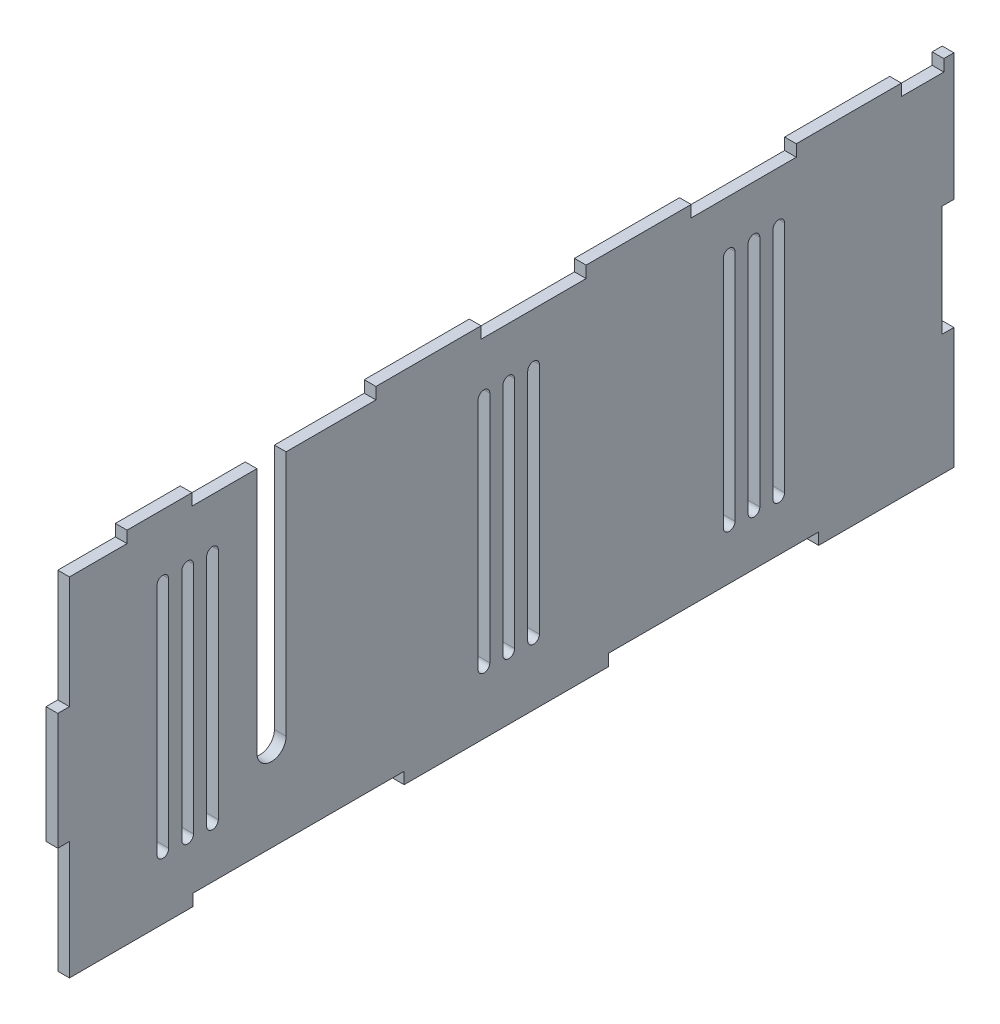
SolidWorks part; units mm, degrees
ref_plane "Front Plane" through (0, 0, 0) normal (0, 0, 1) x (1, 0, 0)
ref_plane "Top Plane" through (0, 0, 0) normal (0, 1, 0) x (1, 0, 0)
ref_plane "Right Plane" through (0, 0, 0) normal (1, 0, 0) x (0, 0, -1)
sketch "Sketch1" plane through (0, 0, 0) normal (1, 0, 0) x (0, 0, -1)
  line L1 (0, 0) -> (307, 0)
  line L2 (0, 0) -> (0, 115)
  line L3 (0, 115) -> (307, 115)
  line L4 (307, 0) -> (307, 115)
  dimension "D1" = 307
  dimension "D2" = 115
extrude "Boss-Extrude1" add sketch "Sketch1" along normal blind 4
sketch "Sketch2" plane through (0, 0, 0) normal (-1, 0, 0) x (0, 0, 1)
  line L0 (-73.2167, 30.5919) -> (-73.2167, 113) construction
  line L1 (-78.2167, 30.5919) -> (-78.2167, 118.2888)
  line L2 (-68.2167, 30.5919) -> (-68.2167, 118.2888)
  line L3 (-139, 113) -> (-121, 113) construction
  line L4 (-78.2167, 118.2888) -> (-68.2167, 118.2888)
  arc A0 (-78.2167, 30.5919) -> (-68.2167, 30.5919) centre (-73.2167, 30.5919) ccw
  point P2 (-73.2167, 71.796)
  dimension "D1" = 10
extrude "Cut-Extrude1" cut sketch "Sketch2" against normal blind 4
sketch "Sketch3" plane through (0, 0, 0) normal (-1, 0, 0) x (0, 0, 1)
  line L0 (0, 36.5) -> (0, -4)
  line L1 (0, 115) -> (-4, 115)
  line L2 (0, 115) -> (0, 76.5)
  line L3 (0, 76.5) -> (-4, 76.5)
  line L4 (-4, 115) -> (-4, 76.5)
  line L9 (0, 36.5) -> (-4, 36.5)
  line L10 (-4, 36.5) -> (-4, -4)
  line L11 (0, 115) -> (0, 0) construction
  line L12 (-68.2167, 115) -> (0, 115) construction
  line L13 (0, -4) -> (-4, -4)
  dimension "D1" = 4
  dimension "D2" = 38.5
  dimension "D3" = 40
extrude "Cut-Extrude2" cut sketch "Sketch3" against normal blind 4
sketch "Sketch4" plane through (0, 0, 0) normal (-1, 0, 0) x (0, 0, 1)
  line L1 (-307, 0) -> (-260.6667, 0)
  line L2 (-307, 0) -> (-307, -4)
  line L3 (-307, -4) -> (-260.6667, -4)
  line L4 (-260.6667, 0) -> (-260.6667, -4)
  line L11 (-4, 0) -> (-46.33, 0)
  line L12 (-4, 0) -> (-4, -4)
  line L13 (-4, -4) -> (-46.33, -4)
  line L14 (-46.33, 0) -> (-46.33, -4)
  dimension "D1" = 46.3333
  dimension "D2" = 4
  dimension "D3" = 42.33
  dimension "D4" = 4
extrude "Boss-Extrude3" add sketch "Sketch4" against normal blind 4 contours L2 L1 L4 L3 | L12 L11 L14 L13
sketch "Sketch5" plane through (0, 0, 0) normal (-1, 0, 0) x (0, 0, 1)
  line L0 (-307, 115) -> (-78.2167, 115) construction
  line L1 (-289, 115) -> (-253, 115)
  line L2 (-289, 115) -> (-289, 119)
  line L3 (-289, 119) -> (-253, 119)
  line L4 (-253, 115) -> (-253, 119)
  line L5 (-307, -4) -> (-307, 115) construction
  dimension "D1" = 4
  dimension "D2" = 36
  dimension "D3" = 18
extrude "Boss-Extrude4" add sketch "Sketch5" against normal blind 4
sketch "Sketch7" plane through (0, 0, 0) normal (-1, 0, 0) x (0, 0, 1)
  line L0 (-68.2167, 115) -> (-4, 115) construction
  line L1 (-45.9767, 115) -> (-23.7367, 115)
  line L2 (-45.9767, 115) -> (-45.9767, 119)
  line L3 (-45.9767, 119) -> (-23.7367, 119)
  line L4 (-23.7367, 115) -> (-23.7367, 119)
  line L5 (-68.2167, 30.5919) -> (-68.2167, 115) construction
  dimension "D1" = 22.24
  dimension "D2" = 22.24
  dimension "D3" = 4
extrude "Boss-Extrude6" add sketch "Sketch7" against normal blind 4
sketch "Sketch8" plane through (0, 0, 0) normal (-1, 0, 0) x (0, 0, 1)
  line L0 (-307, -4) -> (-307, 115) construction
  line L1 (-307, 75.5) -> (-303, 75.5)
  line L2 (-307, 75.5) -> (-307, 37.5)
  line L3 (-307, 37.5) -> (-303, 37.5)
  line L4 (-303, 75.5) -> (-303, 37.5)
  line L5 (-307, 115) -> (-289, 115) construction
  dimension "D1" = 38
  dimension "D2" = 39.5
extrude "Cut-Extrude3" cut sketch "Sketch8" against normal blind 4
pattern_linear "LPattern1" count 3 spacing 72 along (0, 0, 1) of "Boss-Extrude4"
sketch "Sketch9" plane through (0, 0, 0) normal (-1, 0, 0) x (0, 0, 1)
  line L0 (-46.33, 0) -> (-260.6667, 0) construction
  line L1 (-188.6667, 0) -> (-118.6667, 0)
  line L2 (-188.6667, 0) -> (-188.6667, -4)
  line L3 (-188.6667, -4) -> (-118.6667, -4)
  line L4 (-118.6667, 0) -> (-118.6667, -4)
  line L5 (-260.6667, 0) -> (-260.6667, -4) construction
  point P6 (-153.6667, 0)
  dimension "D1" = 70
  dimension "D2" = 107
  dimension "D3" = 4
extrude "Boss-Extrude7" add sketch "Sketch9" against normal blind 4
sketch "Sketch10" plane through (0, 0, 0) normal (-1, 0, 0) x (0, 0, 1)
  line L0 (-247, 97.5) -> (-247, 17.5) construction
  line L1 (-245, 97.5) -> (-245, 17.5)
  line L2 (-249, 97.5) -> (-249, 17.5)
  line L3 (-307, 75.5) -> (-307, 115) construction
  line L4 (-307, -4) -> (-260.6667, -4) construction
  line L6 (-240.5, 97.5) -> (-240.5, 17.5)
  line L7 (-236.5, 97.5) -> (-236.5, 17.5)
  line L8 (-238.5, 97.5) -> (-238.5, 17.5) construction
  line L9 (-232, 97.5) -> (-232, 17.5)
  line L10 (-228, 97.5) -> (-228, 17.5)
  line L11 (-230, 97.5) -> (-230, 17.5) construction
  arc A0 (-245, 97.5) -> (-249, 97.5) centre (-247, 97.5) ccw
  arc A1 (-249, 17.5) -> (-245, 17.5) centre (-247, 17.5) ccw
  arc A2 (-236.5, 97.5) -> (-240.5, 97.5) centre (-238.5, 97.5) ccw
  arc A3 (-240.5, 17.5) -> (-236.5, 17.5) centre (-238.5, 17.5) ccw
  arc A4 (-228, 97.5) -> (-232, 97.5) centre (-230, 97.5) ccw
  arc A5 (-232, 17.5) -> (-228, 17.5) centre (-230, 17.5) ccw
  point P2 (-247, 57.5)
  point P17 (-238.5, 57.5)
  point P24 (-230, 57.5)
  dimension "D1" = 4
  dimension "D2" = 58
  dimension "D3" = 80
  dimension "D4" = 61.5
extrude "Cut-Extrude4" cut sketch "Sketch10" against normal blind 4
pattern_linear "LPattern2" count 2 spacing 84 along (0, 0, 1) of "Cut-Extrude4"
pattern_linear "LPattern3" count 2 spacing 194 along (0, 0, 1) of "Cut-Extrude4"
sketch "Sketch11" plane through (0, 115, 0) normal (0, 1, 0) x (1, 0, 0)
  line L0 (0, 307) -> (0, 289) construction
  line L1 (4, 307) -> (0, 307)
  line L2 (4, 307) -> (4, 303.5424)
  line L3 (4, 303.5424) -> (0, 303.5424)
  line L4 (0, 307) -> (0, 303.5424)
extrude "Boss-Extrude8" add sketch "Sketch11" along normal blind 4
equation "\"Dikte\"= 4"
equation "\"D1@Sketch1\"=135+\"Dikte\" + 2*34 + 2*50"
equation "\"Tolerantie\"= 0.5"
equation "\"D2@Sketch3\"=39-\"Tolerantie\""
equation "\"D3@Sketch3\"=39+2*\"Tolerantie\""
equation "\"D2@Sketch8\"=39+\"Tolerantie\""
equation "\"D1@Sketch8\"=39-2*\"Tolerantie\""
